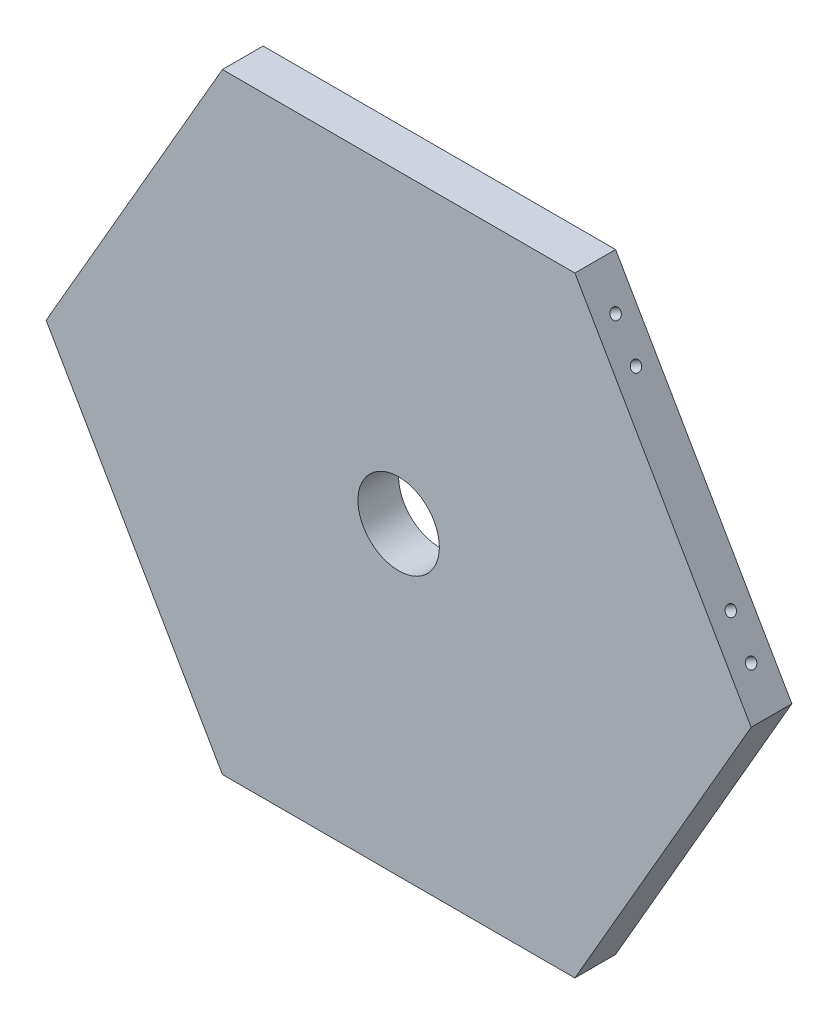
SolidWorks part; units mm, degrees
ref_plane "Front Plane" through (0, 0, 0) normal (0, 0, 1) x (1, 0, 0)
ref_plane "Top Plane" through (0, 0, 0) normal (0, 1, 0) x (1, 0, 0)
ref_plane "Right Plane" through (0, 0, 0) normal (1, 0, 0) x (0, 0, -1)
sketch "Sketch1" plane through (0, 0, 0) normal (0, 0, 1) x (1, 0, 0)
  line L7 (-43.3013, -75) -> (43.3013, -75)
  line L8 (43.3013, -75) -> (86.6025, 0)
  line L9 (86.6025, 0) -> (43.3013, 75)
  line L10 (43.3013, 75) -> (-43.3013, 75)
  line L11 (-43.3013, 75) -> (-86.6025, 0)
  line L12 (-86.6025, 0) -> (-43.3013, -75)
  circle A0 centre (0, 0) radius 75 construction
  dimension "D1" = 150
extrude "Boss-Extrude1" add sketch "Sketch1" along normal mid plane 10
sketch "Sketch2" plane through (0, -75, 0) normal (0, -1, 0) x (1, 0, 0)
  line L0 (-43.3013, 5) -> (-43.3013, -5) construction
  line L1 (-43.3013, -5) -> (43.3013, -5) construction
  line L2 (0, 0) -> (0, 21.4355) construction
  circle A0 centre (-33.3013, 0) radius 1.25
  circle A1 centre (-23.3013, 0) radius 1.25
  circle A2 centre (23.3013, 0) radius 1.25
  circle A3 centre (33.3013, 0) radius 1.25
  dimension "D1" = 2.5
  dimension "D2" = 10
  dimension "D3" = 10
  dimension "D4" = 5
extrude "Cut-Extrude1" cut sketch "Sketch2" against normal blind 10
sketch "Sketch3" plane through (0, 0, 5) normal (0, 0, 1) x (1, 0, 0)
  circle A0 centre (0, 0) radius 10
  dimension "D1" = 20
extrude "Cut-Extrude2" cut sketch "Sketch3" against normal through all
pattern_circular "CirPattern1" count 3 over 360 about axis through (0, 0, 0) along (0, 0, 1) of "Cut-Extrude1"
sketch "Sketch5" plane through (0, 0, 5) normal (0, 0, 1) x (1, 0, 0)
  line L0 (0, 0) -> (86.6025, 0) construction
  line L1 (86.6025, 0) -> (79.1025, 12.9904)
  line L2 (86.6025, 0) -> (43.3013, 75) construction
  line L3 (0, 0) -> (79.1025, 12.9904)
  line L4 (43.3013, 75) -> (50.8013, 62.0096)
  line L5 (-43.3013, 75) -> (-50.8013, 62.0096)
  line L6 (-43.3013, 75) -> (-86.6025, 0) construction
  line L7 (-86.6025, 0) -> (-79.1025, 12.9904)
  line L8 (-43.3013, -75) -> (-28.3013, -75)
  line L9 (-43.3013, -75) -> (43.3013, -75) construction
  line L10 (43.3013, -75) -> (28.3013, -75)
  line L11 (0, 0) -> (50.8013, 62.0096)
  line L12 (0, 0) -> (-50.8013, 62.0096)
  line L13 (0, 0) -> (-79.1025, 12.9904)
  line L14 (0, 0) -> (-28.3013, -75)
  line L15 (0, 0) -> (28.3013, -75)
  line L16 (0, 0) -> (-64.9519, 37.5)
  line L17 (0, 0) -> (64.9519, 37.5)
  line L18 (0, 0) -> (0, -75)
  dimension "D1" = 15
  dimension "D2" = 15
  dimension "D3" = 15
  dimension "D4" = 15
  dimension "D5" = 15
  dimension "D6" = 15
  dimension "D7" = 9.326
  dimension "D8" = 50.674
  dimension "D9" = 129.326
  dimension "D10" = 170.674
  dimension "D11" = 249.326
  dimension "D12" = 290.674
  dimension "D13" = 80.1621
  dimension "D14" = 80.1621
  dimension "D15" = 80.1621
  dimension "D16" = 30
  dimension "D17" = 90
  dimension "D18" = 210
  dimension "D19" = 330
